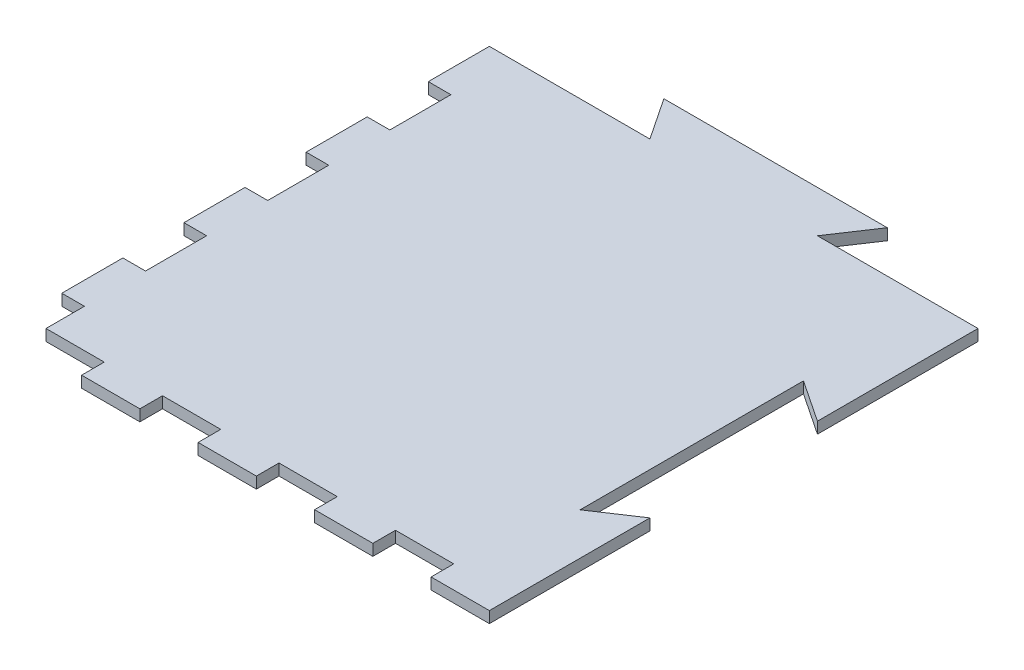
SolidWorks part; units mm, degrees
ref_plane "Front Plane" through (0, 0, 0) normal (0, 0, 1) x (1, 0, 0)
ref_plane "Top Plane" through (0, 0, 0) normal (0, 1, 0) x (1, 0, 0)
ref_plane "Right Plane" through (0, 0, 0) normal (1, 0, 0) x (0, 0, -1)
sketch "Sketch1" plane through (0, 0, 0) normal (0, 1, 0) x (1, 0, 0)
  line L1 (0, 0) -> (222.25, 0)
  line L2 (0, 0) -> (0, 222.25)
  line L3 (0, 222.25) -> (222.25, 222.25)
  line L4 (222.25, 0) -> (222.25, 222.25)
  dimension "D1" = 222.25
extrude "Boss-Extrude1" add sketch "Sketch1" along normal blind 5.15
sketch "Sketch2" plane through (0, 5.15, 0) normal (0, 1, 0) x (1, 0, 0)
  line L0 (0, 0) -> (222.25, 0) construction
  line L1 (10.3, 0) -> (0, 0)
  line L2 (10.3, 0) -> (10.3, 27.7813)
  line L3 (10.3, 27.7813) -> (0, 27.7812)
  line L4 (0, 0) -> (0, 27.7812)
  line L5 (0, 222.25) -> (0, 0) construction
  line L6 (10.3, 27.7813) -> (10.3, 55.5625) construction
  line L7 (10.3, 55.5625) -> (0, 55.5625)
  line L8 (10.3, 55.5625) -> (10.3, 83.3438)
  line L9 (10.3, 83.3438) -> (0, 83.3438)
  line L10 (0, 55.5625) -> (0, 83.3438)
  line L11 (10.3, 83.3438) -> (10.3, 111.125) construction
  line L12 (10.3, 111.125) -> (0, 111.125)
  line L13 (10.3, 111.125) -> (10.3, 138.9062)
  line L14 (10.3, 138.9062) -> (0, 138.9063)
  line L15 (0, 111.125) -> (0, 138.9063)
  line L16 (10.3, 138.9062) -> (10.3, 166.6875) construction
  line L17 (10.3, 166.6875) -> (0, 166.6875)
  line L18 (10.3, 166.6875) -> (10.3, 194.4688)
  line L19 (10.3, 194.4688) -> (0, 194.4688)
  line L20 (0, 166.6875) -> (0, 194.4688)
  line L21 (10.3, 194.4688) -> (10.3, 222.25) construction
  line L22 (222.25, 222.25) -> (0, 222.25) construction
  line L23 (195.7563, 10.3) -> (222.25, 10.3) construction
  line L24 (195.7563, 0) -> (169.2625, 0)
  line L25 (195.7563, 0) -> (195.7563, 10.3)
  line L26 (195.7563, 10.3) -> (169.2625, 10.3)
  line L27 (169.2625, 0) -> (169.2625, 10.3)
  line L28 (222.25, 0) -> (222.25, 222.25) construction
  line L29 (142.7688, 0) -> (116.275, 0)
  line L30 (142.7688, 0) -> (142.7688, 10.3)
  line L31 (142.7688, 10.3) -> (116.275, 10.3)
  line L32 (116.275, 0) -> (116.275, 10.3)
  line L33 (142.7688, 10.3) -> (169.2625, 10.3) construction
  line L34 (89.7813, 0) -> (63.2875, 0)
  line L35 (89.7813, 0) -> (89.7813, 10.3)
  line L36 (89.7813, 10.3) -> (63.2875, 10.3)
  line L37 (63.2875, 0) -> (63.2875, 10.3)
  line L38 (89.7813, 10.3) -> (116.275, 10.3) construction
  line L39 (36.7938, 0) -> (10.3, 0)
  line L40 (36.7938, 0) -> (36.7938, 10.3)
  line L41 (36.7938, 10.3) -> (10.3, 10.3)
  line L42 (10.3, 0) -> (10.3, 10.3)
  line L43 (36.7938, 10.3) -> (63.2875, 10.3) construction
  point P33 (60.0967, 26.1908)
  point P38 (252.4585, 31.8525)
  point P48 (158.3853, 29.3791)
  point P49 (0, 27.7813)
  point P50 (0, 0)
  point P51 (0, 12.908)
  point P52 (0, 10.3)
  point P53 (10.3, 10.3)
  line M25 (0, 222.25) -> (0, 0)
  line M26 (0, 0) -> (222.25, 0)
  dimension "D3" = 10.3
  dimension "D1" = 4
  dimension "D2" = 4
extrude "Cut-Extrude1" cut sketch "Sketch2" against normal through all contours L27 L25 L26 M26 | L32 L30 L31 M26 | L37 L35 L36 M26 | L40 L41 L2 M26 | L2 L3 M25 M26 | L8 L9 L7 M25 | L13 L14 L12 M25 | L18 L19 L20 L17
sketch "Sketch3" plane through (0, 5.15, 0) normal (0, 1, 0) x (1, 0, 0)
  line L0 (73.025, 222.25) -> (60.325, 241.3)
  line L1 (222.25, 222.25) -> (0, 222.25) construction
  line L2 (60.325, 241.3) -> (161.925, 241.3)
  line L3 (161.925, 241.3) -> (149.225, 222.25)
  line L4 (149.225, 222.25) -> (73.025, 222.25)
  point P6 (111.125, 222.25)
  point P7 (111.125, 222.25)
  point P8 (111.125, 222.25)
  point P9 (170.439, 243.1566)
  point P10 (46.4492, 246.2938)
  dimension "D1" = 19.05
  dimension "D2" = 101.6
  dimension "D3" = 76.2
extrude "Boss-Extrude2" add sketch "Sketch3" against normal up to surface (5.15 mm away) up to face at (67.3359, 0, -65.0828)
sketch "Sketch4" plane through (0, 5.15, 0) normal (0, 1, 0) x (1, 0, 0)
  line L0 (222.25, 73.025) -> (203.2, 60.325)
  line L1 (222.25, 0) -> (222.25, 222.25) construction
  line L2 (203.2, 60.325) -> (203.2, 161.925)
  line L3 (203.2, 161.925) -> (222.25, 149.225)
  line L4 (222.25, 149.225) -> (222.25, 73.025)
  line L5 (161.925, 241.3) -> (60.325, 241.3) construction
  line L6 (149.225, 222.25) -> (161.925, 241.3) construction
  line L7 (149.225, 222.25) -> (73.025, 222.25) construction
  point P6 (222.25, 111.125)
  point P7 (222.25, 111.125)
extrude "Cut-Extrude2" cut sketch "Sketch4" against normal through all
equation "\"standard_thickness\"= 5.15mm"
equation "\"D1@Boss-Extrude1\"=\"standard_thickness\""
equation "\"D3@Sketch2\"=\"standard_thickness\"*2"
